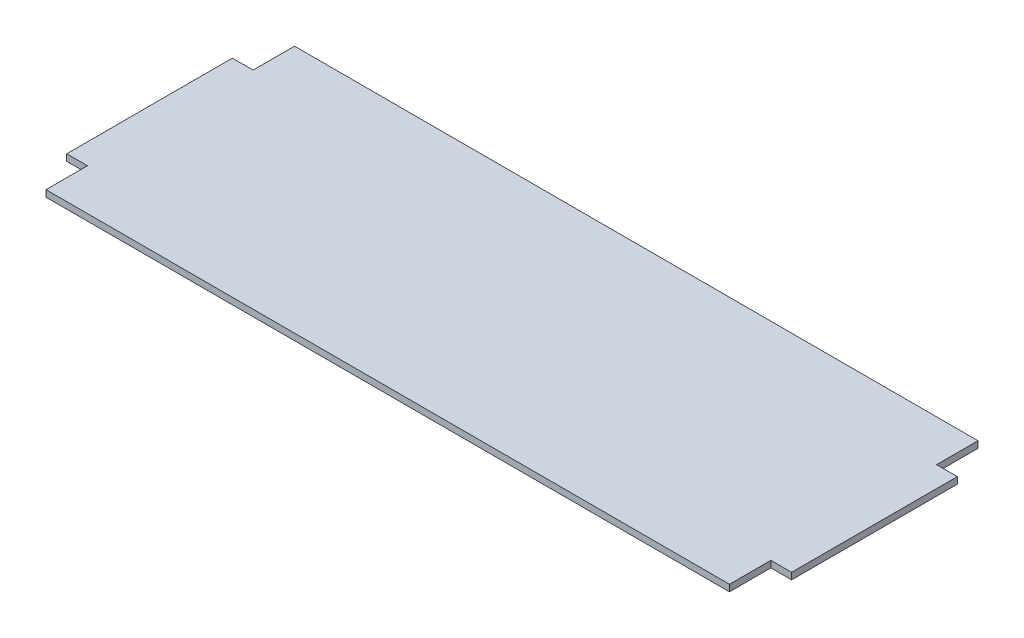
SolidWorks part; units mm, degrees
material "Pine"
ref_plane "Front Plane" through (0, 0, 0) normal (0, 0, 1) x (1, 0, 0)
ref_plane "Top Plane" through (0, 0, 0) normal (0, 1, 0) x (1, 0, 0)
ref_plane "Right Plane" through (0, 0, 0) normal (1, 0, 0) x (0, 0, -1)
sketch "Sketch1" plane through (0, 0, 0) normal (0, 1, 0) x (1, 0, 0)
  line L1 (40, 0) -> (1360, 0)
  line L2 (0, 80) -> (0, 400)
  line L3 (40, 480) -> (1360, 480)
  line L4 (1400, 80) -> (1400, 400)
  line L7 (0, 400) -> (40, 400)
  line L8 (40, 480) -> (40, 400)
  line L11 (0, 80) -> (40, 80)
  line L12 (40, 0) -> (40, 80)
  line L15 (1400, 80) -> (1360, 80)
  line L16 (1360, 0) -> (1360, 80)
  line L19 (1400, 400) -> (1360, 400)
  line L20 (1360, 480) -> (1360, 400)
  dimension "D3" = 80
  dimension "D4" = 40
  dimension "D5" = 80
  dimension "D6" = 40
extrude "Boss-Extrude1" add sketch "Sketch1" along normal blind 12.7
